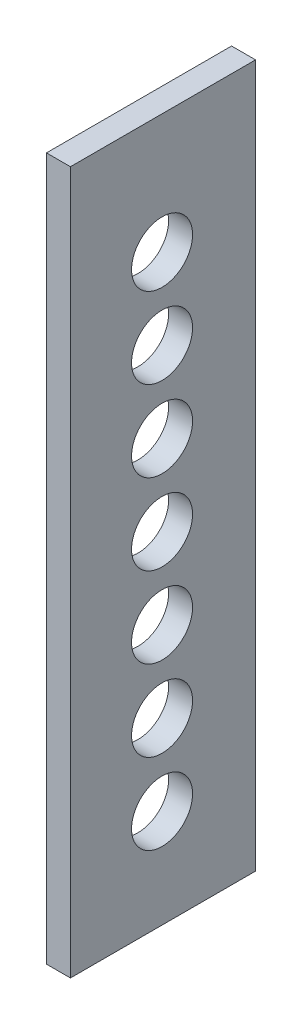
SolidWorks part; units mm, degrees
ref_plane "Спереди" through (0, 0, 0) normal (0, 0, 1) x (1, 0, 0)
ref_plane "Сверху" through (0, 0, 0) normal (0, 1, 0) x (1, 0, 0)
ref_plane "Справа" through (0, 0, 0) normal (1, 0, 0) x (0, 0, -1)
sketch "Эскиз1" plane through (0, 0, 0) normal (1, 0, 0) x (0, 0, -1)
  line L1 (0, 0) -> (42.4617, 0)
  line L2 (0, 0) -> (0, -161.1649)
  line L3 (0, -161.1649) -> (42.4617, -161.1649)
  line L4 (42.4617, 0) -> (42.4617, -161.1649)
  circle A0 centre (21.016, -27.4682) radius 7
  circle A1 centre (21.016, -45.9813) radius 7
  circle A2 centre (21.016, -64.4945) radius 7
  circle A3 centre (21.016, -83.0076) radius 7
  circle A4 centre (21.016, -101.5208) radius 7
  circle A5 centre (21.016, -120.034) radius 7
  circle A6 centre (21.016, -138.5471) radius 7
extrude "Вытянуть1" add sketch "Эскиз1" along normal blind 5.5
